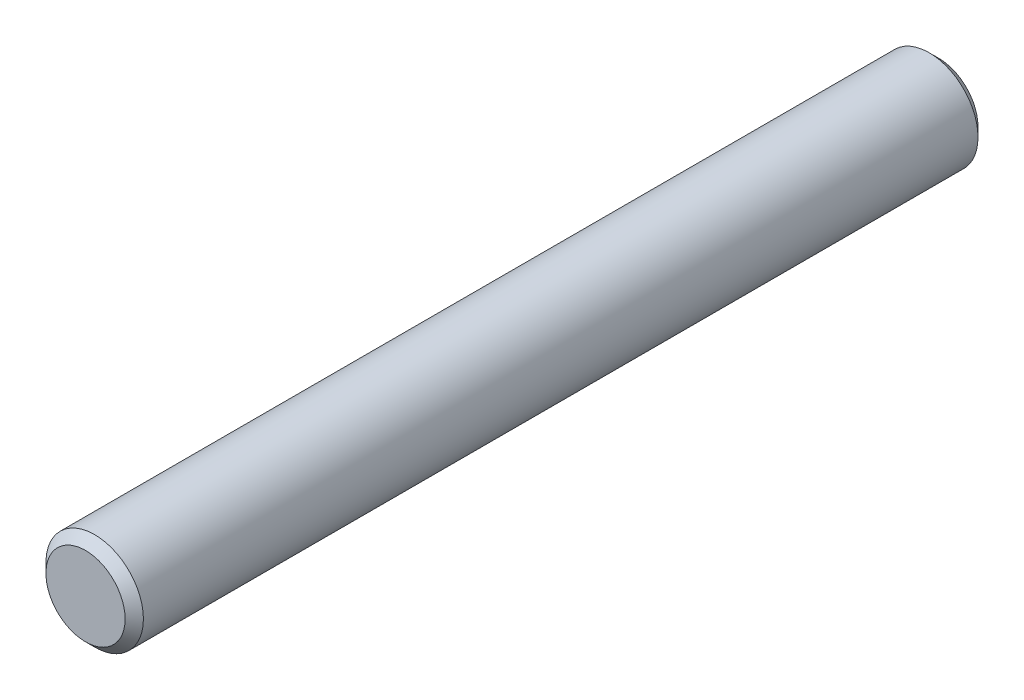
SolidWorks part; units mm, degrees
ref_plane "Front Plane" through (0, 0, 0) normal (0, 0, 1) x (1, 0, 0)
ref_plane "Top Plane" through (0, 0, 0) normal (0, 1, 0) x (1, 0, 0)
ref_plane "Right Plane" through (0, 0, 0) normal (1, 0, 0) x (0, 0, -1)
sketch "Sketch1" plane through (0, 0, 0) normal (0, 0, 1) x (1, 0, 0)
  circle A0 centre (0, 0) radius 4
  dimension "D1" = 8
extrude "Boss-Extrude1" add sketch "Sketch1" along normal blind 70
chamfer "Chamfer1" distance 0.75 angle 45 2 edges at (4, 0, 0) (4, 0, 70)
